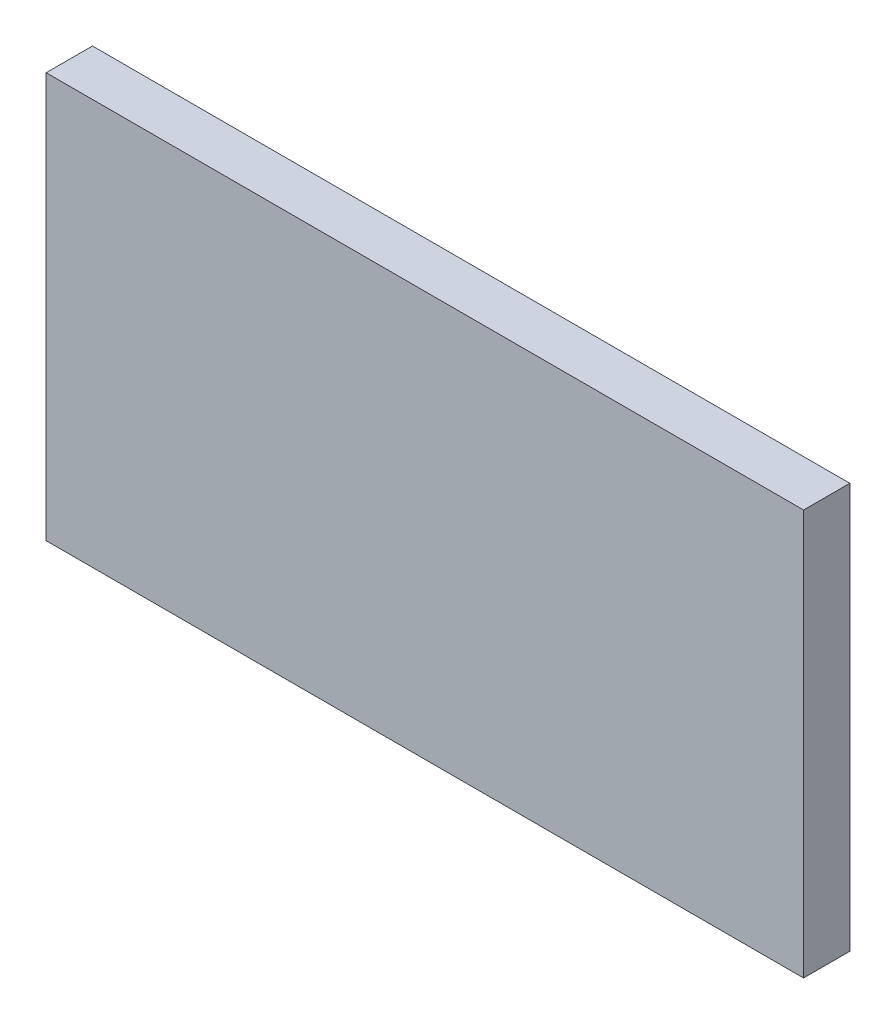
SolidWorks part; units mm, degrees
ref_plane "Front Plane" through (0, 0, 0) normal (0, 0, 1) x (1, 0, 0)
ref_plane "Top Plane" through (0, 0, 0) normal (0, 1, 0) x (1, 0, 0)
ref_plane "Right Plane" through (0, 0, 0) normal (1, 0, 0) x (0, 0, -1)
sketch "Sketch1" plane through (0, 0, 0) normal (0, 0, 1) x (1, 0, 0)
  line L13 (151.4388, -84.8488) -> (-149.6483, -84.8488)
  line L14 (151.4388, -84.8488) -> (151.4388, 75.092)
  line L15 (151.4388, 75.092) -> (-149.6483, 75.092)
  line L16 (-149.6483, -84.8488) -> (-149.6483, 75.092)
  line L18 (152.7088, 76.362) -> (-150.9183, 76.362)
  line L20 (-150.9183, -86.1188) -> (-150.9183, 76.362)
  line L21 (152.7088, -86.1188) -> (-150.9183, -86.1188)
  line L22 (152.7088, -86.1188) -> (152.7088, 76.362)
  arc A0 (137.3979, -83.7102) -> (150.8675, -72.0748) centre (141.9138, -75.3238) ccw construction
  circle A5 centre (-114.6199, 40.0637) radius 35.0284 construction
  point P0 (0, 0)
  dimension "D1" = 1.27
extrude "Boss-Extrude1" add sketch "Sketch1" against normal blind 18.542 contours L21 L22 L18 L20 L13 L16 L15 L14 | L16 L13 L14 L15
